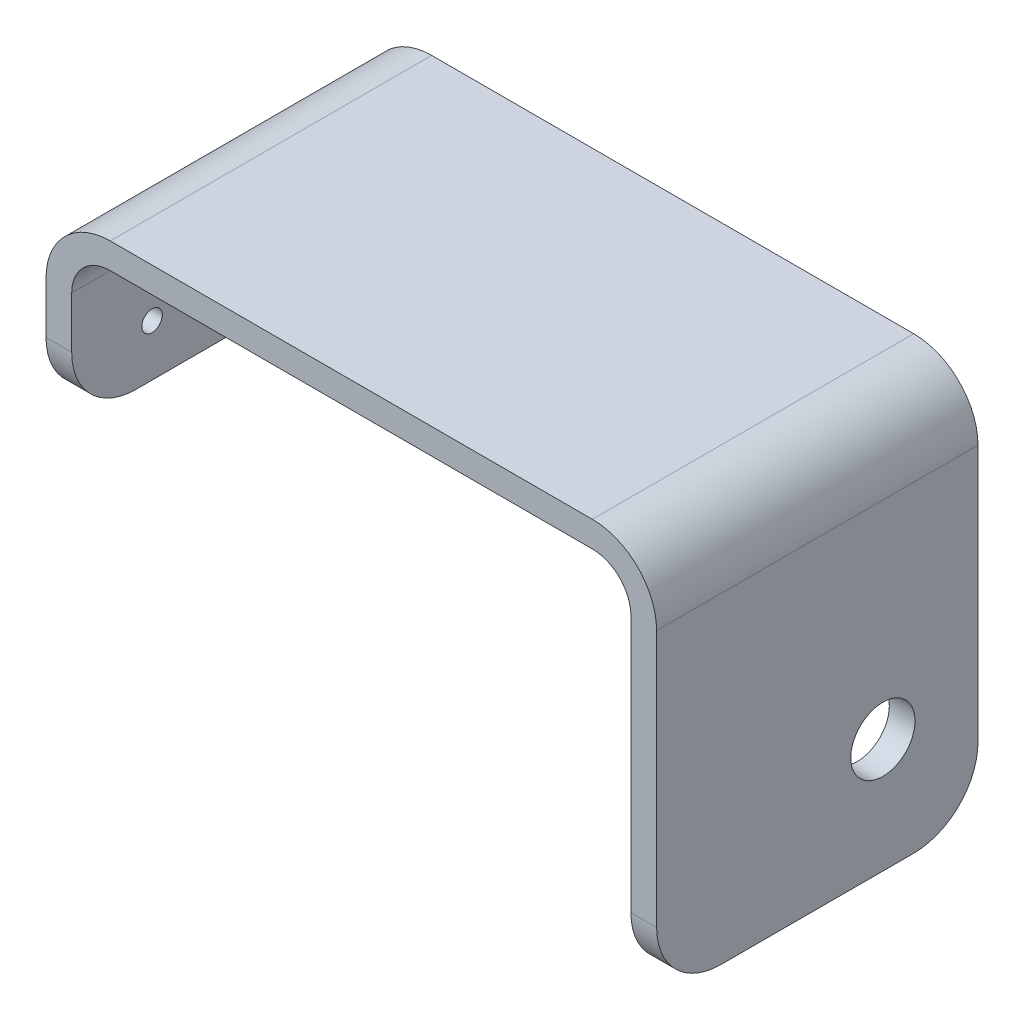
SolidWorks part; units mm, degrees
ref_plane "Front Plane" through (0, 0, 0) normal (0, 0, 1) x (1, 0, 0)
ref_plane "Top Plane" through (0, 0, 0) normal (0, 1, 0) x (1, 0, 0)
ref_plane "Right Plane" through (0, 0, 0) normal (1, 0, 0) x (0, 0, -1)
sketch "Sketch2" plane through (0, 0, 0) normal (0, 0, 1) x (1, 0, 0)
  line L0 (0, 0) -> (-95, 0)
  line L1 (-95, 0) -> (-95, -28)
  line L2 (-95, -28) -> (-91, -28)
  line L3 (-91, -28) -> (-91, -4)
  line L4 (-91, -4) -> (-4, -4)
  line L5 (-4, -4) -> (-4, -60)
  line L6 (-4, -60) -> (0, -60)
  line L7 (0, -60) -> (0, 0)
  dimension "D1" = 4
  dimension "D2" = 4
  dimension "D3" = 4
  dimension "D4" = 95
  dimension "D5" = 28
  dimension "D6" = 60
extrude "Boss-Extrude1" add sketch "Sketch2" along normal blind 50
sketch "Sketch3" plane through (-95, 0, 0) normal (-1, 0, 0) x (0, 0, 1)
  line L0 (0, 0) -> (0, -28) construction
  line L1 (50, 0) -> (50, -28) construction
  line L2 (50, -28) -> (0, -28) construction
  circle A0 centre (12.5, -20) radius 1.6
  circle A1 centre (37.5, -20) radius 1.6
  dimension "D1" = 3.2
  dimension "D2" = 3.2
  dimension "D3" = 25
  dimension "D4" = 12.5
  dimension "D5" = 12.5
  dimension "D6" = 8
extrude "Cut-Extrude1" cut sketch "Sketch3" against normal blind 50
sketch "Sketch4" plane through (0, 0, 0) normal (1, 0, 0) x (0, 0, -1)
  line L1 (-50, 0) -> (0, 0) construction
  line L2 (0, -60) -> (0, 0) construction
  circle A0 centre (-14.8, -42.25) radius 5
  dimension "D1" = 10
  dimension "D2" = 14.8
  dimension "D3" = 42.25
extrude "Cut-Extrude2" cut sketch "Sketch4" against normal blind 50
fillet "Fillet1" radius 10 2 edges at (-95, 0, 25) (0, 0, 25)
fillet "Fillet2" radius 6 2 edges at (-4, -4, 25) (-91, -4, 25)
fillet "Fillet3" radius 10 4 edges at (-2, -60, 50) (-2, -60, 0) (-93, -28, 0) (-93, -28, 50)
